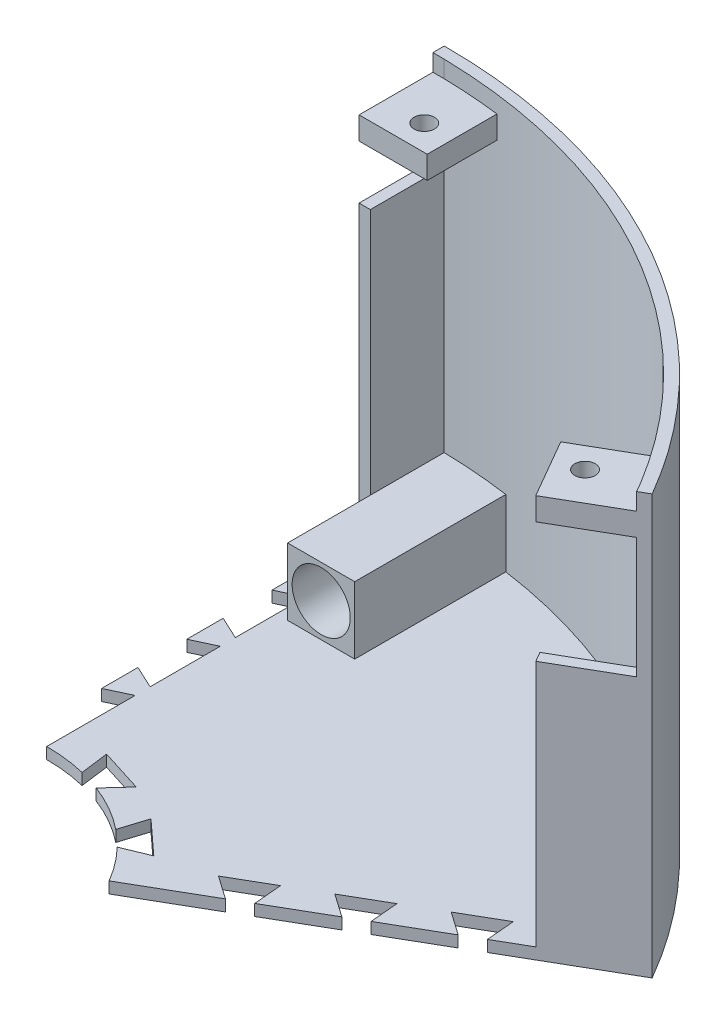
SolidWorks part; units mm, degrees
ref_plane "Front Plane" through (0, 0, 0) normal (0, 0, 1) x (1, 0, 0)
ref_plane "Top Plane" through (0, 0, 0) normal (0, 1, 0) x (1, 0, 0)
ref_plane "Right Plane" through (0, 0, 0) normal (1, 0, 0) x (0, 0, -1)
sketch "Sketch3" plane through (0, 0, 0) normal (0, 1, 0) x (1, 0, 0)
  line L0 (0, 0) -> (0, 127)
  line L1 (0, 0) -> (109.9852, 63.5)
  line L2 (0, 0) -> (109.9852, -63.5) construction
  line L3 (0, 0) -> (0, -127) construction
  line L4 (0, 0) -> (-109.9852, -63.5) construction
  line L5 (0, 0) -> (-109.9852, 63.5) construction
  line L6 (0, 0) -> (25.6661, 44.4549) construction
  line L7 (17.5567, 33.8138) -> (17.5567, 35.489)
  line L8 (17.5567, 35.489) -> (21.9561, 32.949)
  line L9 (21.9561, 32.949) -> (20.5053, 32.1114)
  line L10 (28.6358, 27.344) -> (31.9012, 23.4525)
  line L11 (28.0629, 25.7699) -> (28.6358, 27.344)
  line L12 (31.9012, 23.4525) -> (30.2514, 23.1616)
  line L13 (36.2611, 15.901) -> (37.9985, 11.1273)
  line L14 (35.1843, 14.6177) -> (36.2611, 15.901)
  line L15 (37.9985, 11.1273) -> (36.3488, 11.4182)
  line L16 (39.5127, 2.54) -> (39.5127, -2.54)
  line L17 (38.0619, 1.7024) -> (39.5127, 2.54)
  line L18 (39.5127, -2.54) -> (38.0619, -1.7024)
  line L19 (37.9985, -11.1273) -> (36.2611, -15.901)
  line L20 (36.3488, -11.4182) -> (37.9985, -11.1273)
  line L21 (36.2611, -15.901) -> (35.1843, -14.6177)
  line L22 (31.9012, -23.4525) -> (28.6358, -27.344)
  line L23 (30.2514, -23.1616) -> (31.9012, -23.4525)
  line L24 (28.6358, -27.344) -> (28.0629, -25.7699)
  line L25 (21.9561, -32.949) -> (17.5567, -35.489)
  line L26 (20.5053, -32.1114) -> (21.9561, -32.949)
  line L27 (17.5567, -35.489) -> (17.5567, -33.8138)
  line L28 (9.3627, -38.4714) -> (4.3599, -39.3535)
  line L29 (8.2859, -37.1881) -> (9.3627, -38.4714)
  line L30 (4.3599, -39.3535) -> (4.9329, -37.7793)
  line L31 (-4.3599, -39.3535) -> (-9.3627, -38.4714)
  line L32 (-4.9329, -37.7793) -> (-4.3599, -39.3535)
  line L33 (-9.3627, -38.4714) -> (-8.2859, -37.1881)
  line L34 (-17.5567, -35.489) -> (-21.9561, -32.949)
  line L35 (-17.5567, -33.8138) -> (-17.5567, -35.489)
  line L36 (-21.9561, -32.949) -> (-20.5053, -32.1114)
  line L37 (-28.6358, -27.344) -> (-31.9012, -23.4525)
  line L38 (-28.0629, -25.7699) -> (-28.6358, -27.344)
  line L39 (-31.9012, -23.4525) -> (-30.2514, -23.1616)
  line L40 (-36.2611, -15.901) -> (-37.9985, -11.1273)
  line L41 (-35.1843, -14.6177) -> (-36.2611, -15.901)
  line L42 (-37.9985, -11.1273) -> (-36.3488, -11.4182)
  line L43 (-39.5127, -2.54) -> (-39.5127, 2.54)
  line L44 (-38.0619, -1.7024) -> (-39.5127, -2.54)
  line L45 (-39.5127, 2.54) -> (-38.0619, 1.7024)
  line L46 (-37.9985, 11.1273) -> (-36.2611, 15.901)
  line L47 (-36.3488, 11.4182) -> (-37.9985, 11.1273)
  line L48 (-36.2611, 15.901) -> (-35.1843, 14.6177)
  line L49 (-31.9012, 23.4525) -> (-28.6358, 27.344)
  line L50 (-30.2514, 23.1616) -> (-31.9012, 23.4525)
  line L51 (-28.6358, 27.344) -> (-28.0629, 25.7699)
  line L52 (-21.9561, 32.949) -> (-17.5567, 35.489)
  line L53 (-20.5053, 32.1114) -> (-21.9561, 32.949)
  line L54 (-17.5567, 35.489) -> (-17.5567, 33.8138)
  line L55 (-9.3627, 38.4714) -> (-4.3599, 39.3535)
  line L56 (-8.2859, 37.1881) -> (-9.3627, 38.4714)
  line L57 (-4.3599, 39.3535) -> (-4.9329, 37.7793)
  line L58 (4.3599, 39.3535) -> (9.3627, 38.4714)
  line L59 (4.9329, 37.7793) -> (4.3599, 39.3535)
  line L60 (9.3627, 38.4714) -> (8.2859, 37.1881)
  circle A0 centre (0, 0) radius 127
  circle A1 centre (0, 0) radius 38.1
  point P13 (0, 0)
  point P16 (19.7564, 34.219)
  point P87 (0, 0)
  dimension "D1" = 254
  dimension "D2" = 76.2
  dimension "D7" = 5.08
  dimension "D3" = 6
  dimension "D4" = 30
  dimension "D5" = 60
  dimension "D6" = 60
  dimension "D8" = 18
extrude "Boss-Extrude1" add sketch "Sketch3" along normal blind 2.54 contours A1 L1 A0 L0
sketch "Sketch4" plane through (0, 2.54, 0) normal (0, 1, 0) x (1, 0, 0)
  line L0 (0, 127) -> (0, 107.95)
  line L1 (0, 38.1) -> (0, 127) construction
  line L2 (109.9852, 63.5) -> (93.4874, 53.975)
  line L3 (32.9956, 19.05) -> (109.9852, 63.5) construction
  line L4 (106.5207, 64.4096) -> (92.2274, 56.1574)
  line L5 (2.52, 124.4545) -> (2.52, 107.95)
  line L6 (93.4874, 53.975) -> (92.2274, 56.1574)
  line L7 (0, 107.95) -> (2.52, 107.95)
  arc A0 (109.9852, 63.5) -> (0, 127) centre (0, 0) ccw construction
  arc A1 (109.9852, 63.5) -> (0, 127) centre (0, 0) ccw
  arc A2 (106.5207, 64.4096) -> (2.52, 124.4545) centre (0, 0) ccw
  dimension "D1" = 19.05
  dimension "D2" = 2.52
extrude "Boss-Extrude2" add sketch "Sketch4" along normal blind 91.2
sketch "Sketch5" plane through (0, 2.54, 0) normal (0, 1, 0) x (1, 0, 0)
  line L0 (0, 38.1) -> (32.9956, 19.05) construction
  line L1 (16.356, 28.6569) -> (26.8474, 46.8285) construction
  line L2 (4.5017, 41.395) -> (13.9091, 35.9637) construction
  line L3 (0, 38.1) -> (0, 107.95) construction
  line L4 (32.9956, 19.05) -> (93.4874, 53.975) construction
  line L5 (32.9956, 19.05) -> (93.4874, 53.975)
  line L6 (0, 38.1) -> (0, 107.95)
  line L7 (9.7658, 31.5177) -> (16.0755, 51.5294) construction
  line L8 (21.0837, 25.3813) -> (34.5712, 41.4551) construction
  line L9 (17.8503, 40.2648) -> (8.1606, 43.32)
  line L10 (8.1606, 43.32) -> (8.9894, 37.0243)
  line L11 (17.8503, 40.2648) -> (13.5753, 35.5995)
  line L12 (25.6616, 35.755) -> (23.7751, 29.7717)
  line L13 (25.6616, 35.755) -> (33.1524, 28.891)
  line L14 (33.1524, 28.891) -> (27.3761, 26.4983)
  line L15 (23.9074, 30.1912) -> (34.306, 24.1875) construction
  line L16 (18.9082, 33.0774) -> (19.05, 32.9956) construction
  arc A0 (27.3761, 26.4983) -> (23.7751, 29.7717) centre (0, 0) ccw
  arc A1 (32.9956, 19.05) -> (0, 38.1) centre (0, 0) ccw construction
  arc A2 (19.05, 32.9956) -> (18.908, 33.0771) centre (0, 0) ccw
  arc A3 (13.5753, 35.5995) -> (8.9894, 37.0243) centre (0, 0) ccw
  point P16 (0, 0)
  point P19 (0, 0)
  point P21 (13.0054, 41.7924)
  dimension "D1" = 2
  dimension "D3" = 65
  dimension "D4" = 5.08
  dimension "D5" = 6.35
  dimension "D2" = 2
extrude "Cut-Extrude2" cut sketch "Sketch5" against normal blind 25.908 contours L11 L9 L10 L14 | L14 L13 L12
sketch "Sketch6" plane through (0, 2.54, 0) normal (0, 1, 0) x (1, 0, 0)
  line L0 (49.4934, 28.575) -> (44.2917, 32.2172)
  line L1 (32.9956, 19.05) -> (93.4874, 53.975) construction
  line L2 (44.2917, 32.2172) -> (53.0906, 37.2972)
  line L3 (53.0906, 37.2972) -> (53.644, 30.9714)
  line L4 (49.4934, 28.575) -> (53.644, 30.9714)
  line L5 (32.9956, 19.05) -> (93.4874, 53.975) construction
  line L6 (65.9911, 38.1) -> (70.1418, 40.4964)
  line L7 (69.5883, 46.8222) -> (70.1418, 40.4964)
  line L8 (60.7895, 41.7422) -> (69.5883, 46.8222)
  line L9 (65.9911, 38.1) -> (60.7895, 41.7422)
  line L10 (82.4889, 47.625) -> (86.6396, 50.0214)
  line L11 (86.0861, 56.3472) -> (86.6396, 50.0214)
  line L12 (77.2873, 51.2672) -> (86.0861, 56.3472)
  line L13 (82.4889, 47.625) -> (77.2873, 51.2672)
  line L14 (0, 95.9672) -> (0, 99.3256)
  line L15 (-5.7551, 102.7264) -> (0, 100.0427) construction
  line L16 (-5.7551, 92.5664) -> (-5.7551, 102.7264) construction
  line L17 (0, 95.25) -> (-5.7551, 92.5664) construction
  line L18 (0, 76.9172) -> (0, 80.2756)
  line L19 (-5.7551, 83.6764) -> (0, 80.9927) construction
  line L20 (-5.7551, 73.5164) -> (-5.7551, 83.6764) construction
  line L21 (0, 76.2) -> (-5.7551, 73.5164) construction
  line L22 (0, 57.8672) -> (0, 61.2256)
  line L23 (-5.7551, 64.6264) -> (0, 61.9427) construction
  line L24 (-5.7551, 54.4664) -> (-5.7551, 64.6264) construction
  line L25 (0, 57.15) -> (-5.7551, 54.4664) construction
  line L26 (0, 57.8672) -> (-5.1051, 55.4867)
  line L27 (-5.1051, 55.4867) -> (-5.1051, 63.6061)
  line L28 (-5.1051, 63.6061) -> (0, 61.2256)
  line L29 (0, 76.9172) -> (-5.1051, 74.5367)
  line L30 (-5.1051, 74.5367) -> (-5.1051, 82.6561)
  line L31 (-5.1051, 82.6561) -> (0, 80.2756)
  line L32 (0, 95.9672) -> (-5.1051, 93.5867)
  line L33 (-5.1051, 93.5867) -> (-5.1051, 101.7061)
  line L34 (-5.1051, 101.7061) -> (0, 99.3256)
  line L35 (-5.1051, 101.7061) -> (-0.2747, 99.4536) construction
  line L36 (-0.2747, 95.8391) -> (-5.1051, 93.5867) construction
  line L37 (-5.1051, 82.6561) -> (-0.2747, 80.4036) construction
  line L38 (-0.2747, 76.7891) -> (-5.1051, 74.5367) construction
  line L39 (-5.1051, 63.6061) -> (-0.2747, 61.3536) construction
  line L40 (-0.2747, 57.7391) -> (-5.1051, 55.4867) construction
  point P31 (0, 0)
  dimension "D1" = 10.16
  dimension "D2" = 65
  dimension "D3" = 65
  dimension "D4" = 6.35
  dimension "D5" = 19.05
  dimension "D6" = 3
  dimension "D10" = 5.7551
  dimension "D11" = 5.7551
  dimension "D12" = 5.7551
  dimension "D13" = 4.7927
  dimension "D14" = 10.16
  dimension "D8" = 0.65
  dimension "D7" = 2
extrude "Cut-Extrude3" cut sketch "Sketch6" against normal blind 25.908 contours L4 L3 L2 L0 | L6 L7 L8 L9 | L10 L11 L12 L13
sketch "Sketch7" plane through (0, 2.54, 0) normal (0, 1, 0) x (1, 0, 0)
  line L0 (-5.7551, 102.7264) -> (0, 100.0427) construction
  line L1 (0, 95.25) -> (-5.7551, 92.5664) construction
  line L2 (-5.7551, 92.5664) -> (-5.7551, 102.7264) construction
  line L3 (0, 76.2) -> (-5.7551, 73.5164) construction
  line L4 (-5.7551, 73.5164) -> (-5.7551, 83.6764) construction
  line L5 (-5.7551, 83.6764) -> (0, 80.9927) construction
  line L6 (-5.7551, 64.6264) -> (0, 61.9427) construction
  line L7 (0, 57.15) -> (-5.7551, 54.4664) construction
  line L8 (-5.7551, 54.4664) -> (-5.7551, 64.6264) construction
  line L9 (-5.1051, 63.6061) -> (0, 61.2256) construction
  line L10 (0, 57.8672) -> (0, 61.2256) construction
  line L11 (0, 57.8672) -> (-5.1051, 55.4867) construction
  line L12 (-5.1051, 55.4867) -> (-5.1051, 63.6061) construction
  line L13 (-5.1051, 82.6561) -> (0, 80.2756) construction
  line L14 (0, 76.9172) -> (0, 80.2756) construction
  line L15 (0, 76.9172) -> (-5.1051, 74.5367) construction
  line L16 (-5.1051, 74.5367) -> (-5.1051, 82.6561) construction
  line L17 (0, 95.9672) -> (0, 99.3256) construction
  line L18 (-5.1051, 101.7061) -> (0, 99.3256) construction
  line L19 (-5.1051, 93.5867) -> (-5.1051, 101.7061) construction
  line L20 (0, 95.9672) -> (-5.1051, 93.5867) construction
  line L21 (-5.7551, 102.7264) -> (0, 100.0427)
  line L22 (0, 95.25) -> (-5.7551, 92.5664)
  line L23 (-5.7551, 92.5664) -> (-5.7551, 102.7264)
  line L24 (0, 76.2) -> (-5.7551, 73.5164)
  line L25 (-5.7551, 73.5164) -> (-5.7551, 83.6764)
  line L26 (-5.7551, 83.6764) -> (0, 80.9927)
  line L27 (-5.7551, 64.6264) -> (0, 61.9427)
  line L28 (0, 57.15) -> (-5.7551, 54.4664)
  line L29 (-5.7551, 54.4664) -> (-5.7551, 64.6264)
  line L30 (-5.1051, 63.6061) -> (0, 61.2256)
  line L31 (0, 57.8672) -> (0, 61.2256)
  line L32 (0, 57.8672) -> (-5.1051, 55.4867)
  line L33 (-5.1051, 55.4867) -> (-5.1051, 63.6061)
  line L34 (-5.1051, 82.6561) -> (0, 80.2756)
  line L35 (0, 76.9172) -> (0, 80.2756)
  line L36 (0, 76.9172) -> (-5.1051, 74.5367)
  line L37 (-5.1051, 74.5367) -> (-5.1051, 82.6561)
  line L38 (0, 95.9672) -> (0, 99.3256)
  line L39 (-5.1051, 101.7061) -> (0, 99.3256)
  line L40 (-5.1051, 93.5867) -> (-5.1051, 101.7061)
  line L41 (0, 95.9672) -> (-5.1051, 93.5867)
  line M19 (0, 107.95) -> (0, 38.1)
extrude "Boss-Extrude3" add sketch "Sketch7" against normal up to surface (2.54 mm away) contours L41 L39 L40 M19 | L37 L36 L34 M19 | L33 L32 L30 M19 up to face at (46.252, 0, -43.4095)
sketch "Sketch9" plane through (0, 93.74, 0) normal (0, 1, 0) x (1, 0, 0)
  line L0 (2.52, 107.95) -> (15.24, 107.95)
  line L1 (15.24, 123.5436) -> (15.24, 107.95)
  line L2 (2.52, 107.95) -> (2.52, 124.4545) construction
  line L3 (2.52, 107.95) -> (2.52, 124.4545) construction
  line L4 (2.52, 107.95) -> (2.52, 124.4545)
  line L5 (2.52, 107.95) -> (2.52, 124.4545)
  line L6 (44.0656, 25.4413) -> (0, 0) construction
  line L7 (92.2274, 56.1574) -> (85.8674, 67.1732)
  line L8 (19.05, 32.9956) -> (26.8474, 46.8285) construction
  line L9 (0, 38.1) -> (0, 107.95) construction
  line L10 (0, 41.305) -> (0, 0) construction
  line L11 (32.9956, 19.05) -> (93.4874, 53.975) construction
  line L12 (0, 0) -> (62.24, 107.8028) construction
  line L13 (99.3719, 74.97) -> (85.8674, 67.1732)
  arc A0 (106.5207, 64.4096) -> (2.52, 124.4545) centre (0, 0) ccw construction
  arc A1 (106.5207, 64.4096) -> (2.52, 124.4545) centre (0, 0) ccw construction
  arc A2 (106.5207, 64.4096) -> (2.52, 124.4545) centre (0, 0) ccw
  line M6 (2.52, 107.95) -> (2.52, 124.4545)
  arc M7 (2.52, 124.4545) -> (106.5207, 64.4096) centre (0, 0) cw
  line M8 (106.5207, 64.4096) -> (92.2274, 56.1574)
  dimension "D1" = 30
extrude "Boss-Extrude6" add sketch "Sketch9" against normal blind 5.08 from offset 3.81 contours L1 L0 M7 M6 | L13 L7 M7 M8 offset against normal yes
sketch "Sketch12" plane through (0, 89.93, 0) normal (0, 1, 0) x (1, 0, 0)
  line L0 (0, 127) -> (0, 107.95) construction
  line L2 (8.89, 113.6272) -> (8.89, 107.95) construction
  line L3 (2.52, 107.95) -> (15.24, 107.95) construction
  line L4 (0, 0) -> (62.24, 107.8028) construction
  line L5 (0, 127) -> (8.89, 113.6272) construction
  circle A0 centre (8.89, 113.6272) radius 2.286
  circle A1 centre (93.959, 64.5125) radius 2.286
  dimension "D1" = 8.89
  dimension "D2" = 16.0582
  dimension "D3" = 33.615
extrude "Cut-Extrude4" cut sketch "Sketch12" against normal up to next
sketch "Sketch14" plane through (0, 93.74, 0) normal (0, 1, 0) x (1, 0, 0)
  line L0 (2.52, 124.4545) -> (0, 124.4545)
  line L1 (0, 127) -> (0, 107.95) construction
  line L2 (0, 0) -> (62.24, 107.8028) construction
  line L4 (106.5207, 64.4096) -> (107.7807, 62.2272)
  line L6 (0, 124.4545) -> (0, 107.95)
  line L7 (0, 107.95) -> (2.52, 107.95)
  line L8 (2.52, 107.95) -> (2.52, 124.4545)
  line L9 (93.4874, 53.975) -> (92.2274, 56.1574)
  line L10 (107.7807, 62.2272) -> (93.4874, 53.975)
  line L11 (92.2274, 56.1574) -> (106.5207, 64.4096)
extrude "Cut-Extrude5" cut sketch "Sketch14" against normal up to surface (3.81 mm away) up to face at (8.89, 89.93, -111.3412)
sketch "Sketch16" plane through (0, 89.93, 0) normal (0, 1, 0) x (1, 0, 0)
  circle A0 centre (0, 0) radius 113.9744 construction
  circle A1 centre (8.89, 113.6272) radius 2.286 construction
  circle A2 centre (8.89, 113.6272) radius 2.286
sketch "Sketch20" plane through (0, 0, -107.95) normal (0, 0, 1) x (1, 0, 0)
  line L0 (0, 89.93) -> (0, 2.54) construction
  line L1 (2.52, 84.85) -> (0, 84.85)
  line L2 (2.52, 84.85) -> (2.52, 72.85)
  line L3 (2.52, 72.85) -> (0, 72.85)
  line L4 (0, 84.85) -> (0, 72.85)
  dimension "D1" = 2.52
  dimension "D2" = 12
extrude "Cut-Extrude8" cut sketch "Sketch20" against normal up to vertex (16.5045 mm away) contours L2 L1 L4 L3 up to point (2.52, 84.85, -124.4545)
sketch "Sketch21" plane through (93.4874, 0, -53.975) normal (-0.866, 0, 0.5) x (0.5, 0, 0.866)
  line L0 (0, 89.93) -> (0, 2.54) construction
  line L1 (-2.52, 84.85) -> (0, 84.85)
  line L2 (-2.52, 84.85) -> (-2.52, 57.85)
  line L3 (-2.52, 57.85) -> (0, 57.85)
  line L4 (0, 84.85) -> (0, 57.85)
extrude "Cut-Extrude9" cut sketch "Sketch21" against normal up to vertex (16.5045 mm away) contours L2 L1 L4 L3 up to point (106.5207, 84.85, -64.4096)
sketch "Sketch22" plane through (0, 2.54, 0) normal (0, 1, 0) x (1, 0, 0)
  line L2 (2.52, 124.4545) -> (2.52, 89.4545)
  line L3 (2.52, 89.4545) -> (17.52, 89.4545)
  line L4 (17.52, 123.2409) -> (17.52, 89.4545)
  arc A0 (106.5207, 64.4096) -> (2.52, 124.4545) centre (0, 0) ccw construction
  arc A1 (17.52, 123.2409) -> (2.52, 124.4545) centre (0, 0) ccw
  dimension "D1" = 35
  dimension "D2" = 15
extrude "Boss-Extrude7" add sketch "Sketch22" along normal blind 15
sketch "Sketch23" plane through (0, 0, -89.4545) normal (0, 0, 1) x (1, 0, 0)
  line L0 (10.02, 17.54) -> (10.02, 2.54) construction
  line L1 (17.52, 17.54) -> (2.52, 17.54) construction
  line L2 (17.8503, 2.54) -> (8.1606, 2.54) construction
  line L3 (17.52, 10.04) -> (2.52, 10.04) construction
  line L4 (17.52, 17.54) -> (17.52, 2.54) construction
  line L5 (2.52, 17.54) -> (2.52, 2.54) construction
  circle A0 centre (10.02, 10.04) radius 6.5
extrude "Cut-Extrude10" cut sketch "Sketch23" against normal up to next contours A0
